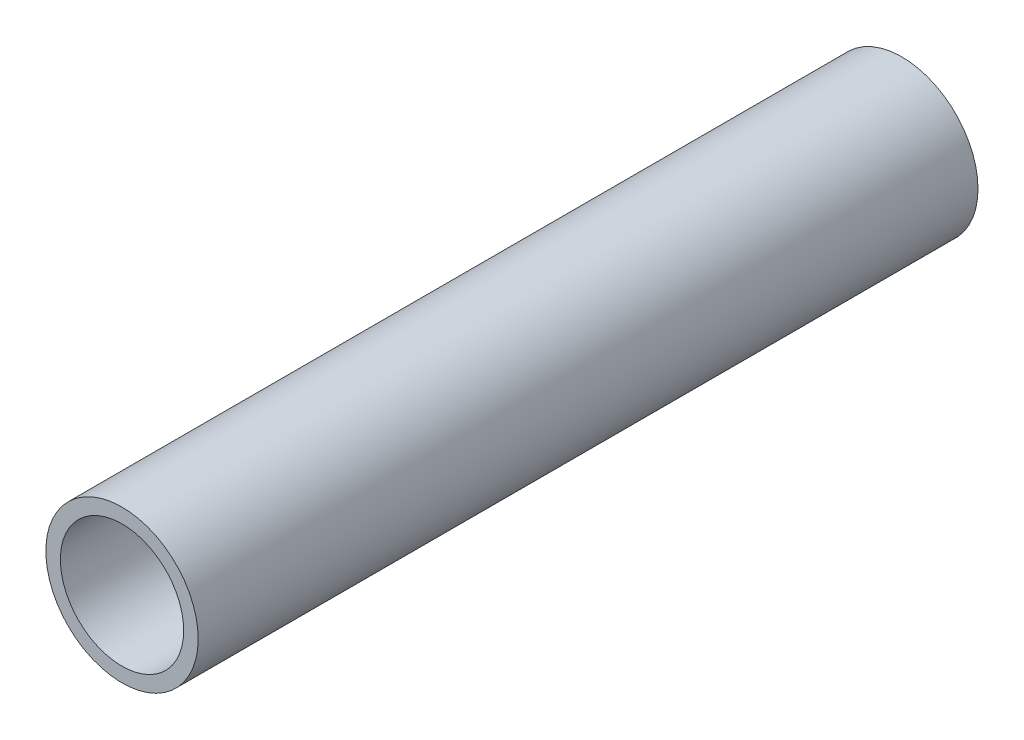
SolidWorks part; units mm, degrees
material "AISI 304"
ref_plane "Спереди" through (0, 0, 0) normal (0, 0, 1) x (1, 0, 0)
ref_plane "Сверху" through (0, 0, 0) normal (0, 1, 0) x (1, 0, 0)
ref_plane "Справа" through (0, 0, 0) normal (1, 0, 0) x (0, 0, -1)
other "Configuration Table"
sketch "Эскиз1" plane through (0, 0, 0) normal (0, 0, 1) x (1, 0, 0)
  circle A0 centre (0, 0) radius 21
  circle A1 centre (0, 0) radius 17
  dimension "D1" = 42
  dimension "D2" = 4
extrude "Бобышка-Вытянуть1" add sketch "Эскиз1" along normal blind 215
move or copy body "Тело-Переместить/Копировать2" [suppressed] bodies to move or copy 103 parameters "D1"=0, "D2"=0, "D3"=0
move or copy body "Тело-Переместить/Копировать1" [suppressed] bodies to move or copy 103 parameters "D1"=0, "D2"=0, "D3"=0
